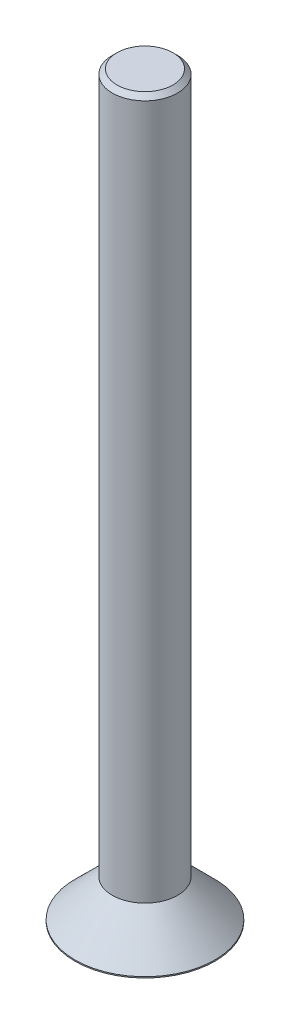
SolidWorks part; units mm, degrees
ref_plane "前视基准面" through (0, 0, 0) normal (0, 0, 1) x (1, 0, 0)
ref_plane "上视基准面" through (0, 0, 0) normal (0, 1, 0) x (1, 0, 0)
ref_plane "右视基准面" through (0, 0, 0) normal (1, 0, 0) x (0, 0, -1)
sketch "草图1" plane through (0, 0, 0) normal (0, 1, 0) x (1, 0, 0)
  circle A0 centre (0, 0) radius 3
  dimension "D1" = 6
extrude "凸台-拉伸1" add sketch "草图1" along normal blind 1.65
chamfer "倒角1" distance 1.6 angle 45 1 edges at (0, 1.65, 3)
sketch "草图2" plane through (0, 0, 0) normal (0, -1, 0) x (1, 0, 0)
  line L1 (1, -0.5774) -> (1, 0.5774)
  line L2 (1, 0.5774) -> (0, 1.1547)
  line L3 (0, 1.1547) -> (-1, 0.5774)
  line L4 (-1, 0.5774) -> (-1, -0.5774)
  line L5 (-1, -0.5774) -> (0, -1.1547)
  line L6 (0, -1.1547) -> (1, -0.5774)
  circle A0 centre (0, 0) radius 1 construction
  dimension "D1" = 2
extrude "切除-拉伸1" cut sketch "草图2" against normal blind 0.95
sketch "草图3" plane through (0, 1.65, 0) normal (0, 1, 0) x (1, 0, 0)
  circle A0 centre (0, 0) radius 1.4
  dimension "D1" = 2.8
extrude "凸台-拉伸2" add sketch "草图3" along normal blind 30
chamfer "倒角2" distance 0.2 angle 45 1 edges at (0, 31.65, 1.4)
